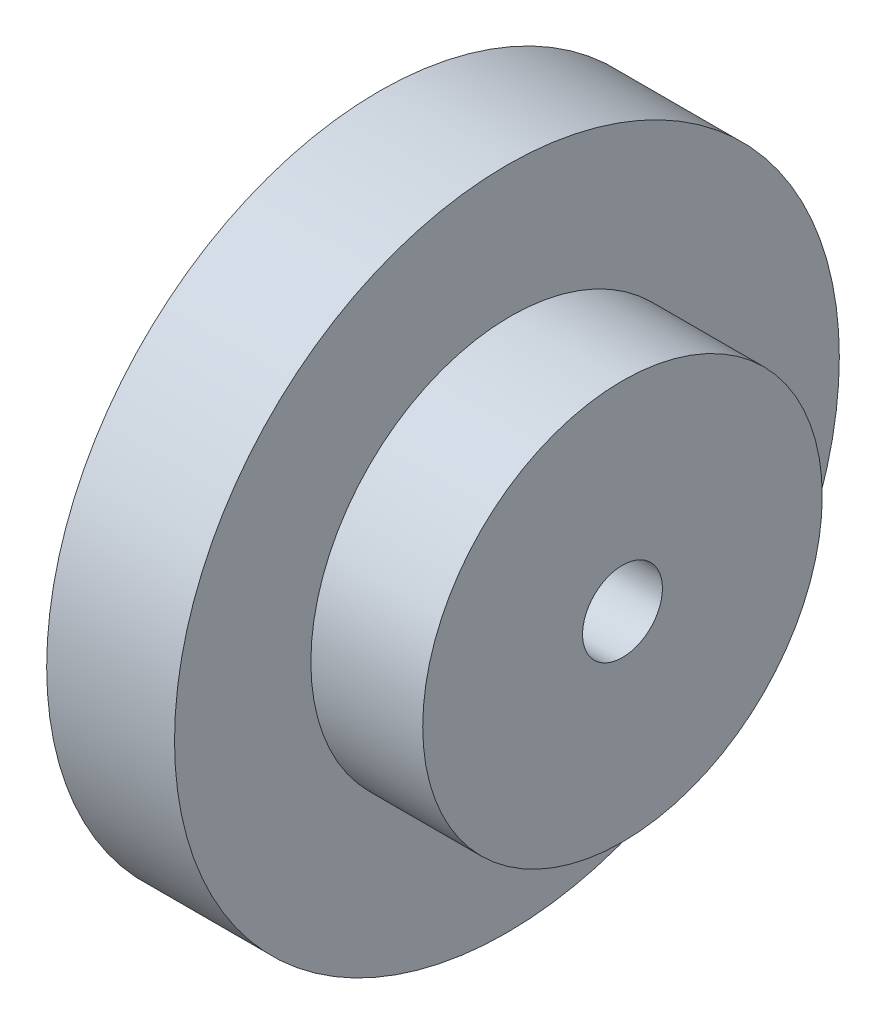
SolidWorks part; units mm, degrees
material "AISI 1035 Steel (SS)"
ref_plane "Front" through (0, 0, 0) normal (0, 0, 1) x (1, 0, 0)
ref_plane "Top" through (0, 0, 0) normal (0, 1, 0) x (1, 0, 0)
ref_plane "Right" through (0, 0, 0) normal (1, 0, 0) x (0, 0, -1)
sketch "Sketch1" plane through (0, 0, 0) normal (1, 0, 0) x (0, 0, -1)
  circle A0 centre (0, -0.1972) radius 20.8
  circle A1 centre (0.2308, -0.1972) radius 2.5
  dimension "D1" = 41.6
  dimension "D2" = 5
extrude "Boss-Extrude1" add sketch "Sketch1" along normal blind 8
sketch "Sketch2" plane through (8, 0, 0) normal (1, 0, 0) x (0, 0, -1)
  circle A0 centre (0.2308, -0.1972) radius 12.5
  circle A2 centre (0.2308, -0.1972) radius 2.5
  dimension "D1" = 25
  dimension "D2" = 5
extrude "Boss-Extrude3" add sketch "Sketch2" along normal blind 7
